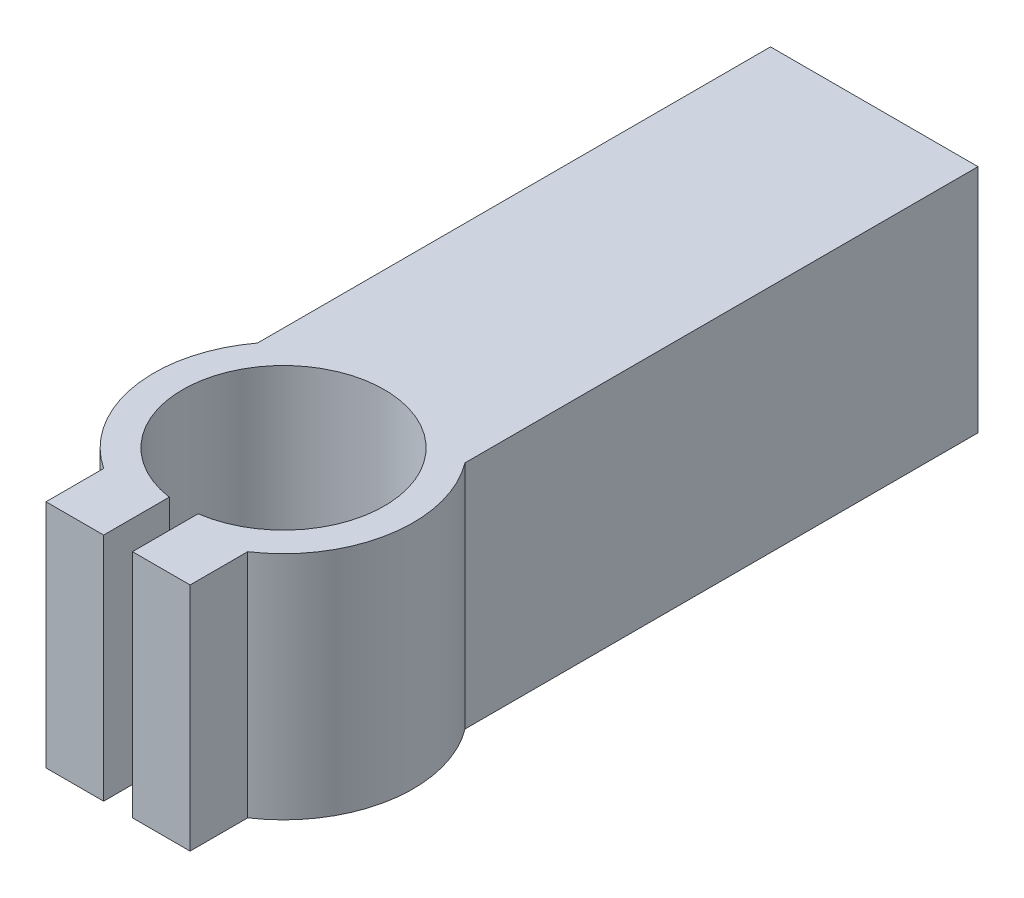
SolidWorks part; units mm, degrees
ref_plane "Front Plane" through (0, 0, 0) normal (0, 0, 1) x (1, 0, 0)
ref_plane "Top Plane" through (0, 0, 0) normal (0, 1, 0) x (1, 0, 0)
ref_plane "Right Plane" through (0, 0, 0) normal (1, 0, 0) x (0, 0, -1)
sketch "Sketch1" plane through (0, 0, 0) normal (0, 1, 0) x (1, 0, 0)
  line L1 (0, 0) -> (45.72, 0)
  line L2 (0, 0) -> (0, 101.6)
  line L3 (0, 101.6) -> (45.72, 101.6)
  line L4 (45.72, 0) -> (45.72, 101.6)
  dimension "D1" = 45.72
  dimension "D2" = 101.6
extrude "Boss-Extrude1" add sketch "Sketch1" along normal blind 50.8
sketch "Sketch4" plane through (0, 0, 0) normal (0, -1, 0) x (1, 0, 0)
  line L0 (0, 0) -> (0, 11.43)
  line L1 (0, 0) -> (45.72, 0)
  line L2 (19.685, 50.572) -> (19.685, 65.0345)
  line L3 (26.035, 50.572) -> (26.035, 65.0345)
  line L4 (26.035, 65.0345) -> (38.735, 65.0345)
  line L5 (38.735, 65.0345) -> (38.735, 52.3345)
  line L7 (19.685, 65.0345) -> (6.985, 65.0345)
  line L8 (6.985, 65.0345) -> (6.985, 52.3345)
  line L9 (0, 0) -> (45.72, 0) construction
  line L10 (45.72, 0) -> (45.72, 11.43)
  arc A2 (19.685, 50.572) -> (26.035, 50.572) centre (22.86, 28.575) ccw
  arc A4 (6.985, 52.3345) -> (0, 11.43) centre (22.86, 28.575) ccw
  arc A5 (38.735, 52.3345) -> (45.72, 11.43) centre (22.86, 28.575) cw
  point P7 (22.86, 0)
  point P11 (22.86, 0)
  dimension "D2" = 22.225
  dimension "D3" = 6.35
  dimension "D4" = 12.7
  dimension "D5" = 12.7
extrude "Boss-Extrude2" add sketch "Sketch4" against normal blind 50.8 contours L3 L4 L5 A5 L10 L1 L0 A4 L8 L7 L2 A2
equation "\"D1@Sketch1\"=\"ArmBaseWidth@Thruster.Assembly\"-2*(\"BracketThickness@Thruster.Assembly\")"
equation "\"D2@Sketch1\"=\"ArmBaseWidth@Thruster.Assembly\"*2"
equation "\"D1@Boss-Extrude1\"=\"ArmBaseWidth@Thruster.Assembly\""
